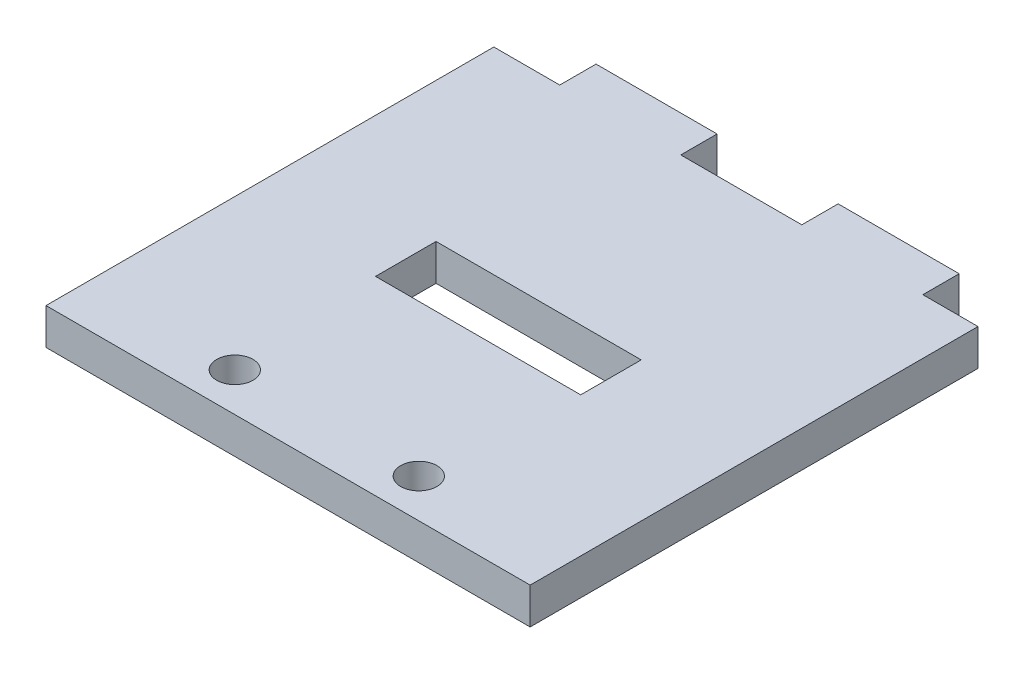
SolidWorks part; units mm, degrees
ref_plane "Front Plane" through (0, 0, 0) normal (0, 0, 1) x (1, 0, 0)
ref_plane "Top Plane" through (0, 0, 0) normal (0, 1, 0) x (1, 0, 0)
ref_plane "Right Plane" through (0, 0, 0) normal (1, 0, 0) x (0, 0, -1)
sketch "Sketch1" plane through (0, 0, 0) normal (0, 1, 0) x (1, 0, 0)
  line L1 (-20, 20) -> (20, 20)
  line L2 (-20, 20) -> (-20, -20)
  line L3 (-20, -20) -> (20, -20)
  line L4 (20, 20) -> (20, -20)
  line L5 (-20, 20) -> (20, -20) construction
  line L6 (-20, -20) -> (20, 20) construction
  point P0 (0, 0)
  dimension "D1" = 40
  dimension "D2" = 40
extrude "Boss-Extrude1" add sketch "Sketch1" along normal blind 3
sketch "Sketch2" plane through (0, 0, 0) normal (0, -1, 0) x (1, 0, 0)
  line L0 (-20, 16.8) -> (20, 16.8) construction
  line L1 (-20, -20) -> (-20, 20) construction
  line L2 (20, 20) -> (20, -20) construction
  line L3 (20, -20) -> (-20, -20) construction
  line L4 (0, 20) -> (0, -20) construction
  line L5 (-20, 20) -> (20, 20) construction
  line L7 (8.4755, -0.7) -> (-8.4755, -0.7)
  line L8 (8.4755, -0.7) -> (8.4755, 4.3)
  line L9 (8.4755, 4.3) -> (-8.4755, 4.3)
  line L10 (-8.4755, -0.7) -> (-8.4755, 4.3)
  line L11 (8.4755, -0.7) -> (-8.4755, 4.3) construction
  line L12 (8.4755, 4.3) -> (-8.4755, -0.7) construction
  circle A0 centre (7.6, 16.8) radius 1.5
  circle A1 centre (-7.6, 16.8) radius 1.5
  point P16 (0, 1.8)
  dimension "D6" = 3
  dimension "D7" = 3
  dimension "D1" = 21.8
  dimension "D2" = 7.6
  dimension "D3" = 7.6
  dimension "D4" = 17.5
  dimension "D5" = 5
extrude "Cut-Extrude2" cut sketch "Sketch2" against normal blind 10
sketch "Sketch5" plane through (0, 0, 0) normal (0, -1, 0) x (1, 0, 0)
  line L0 (20, -17) -> (15.4445, -17)
  line L1 (20, 20) -> (20, -20) construction
  line L2 (-20.6555, -17) -> (32.3445, -17) construction
  line L3 (15.4445, -17) -> (15.4445, -20)
  line L4 (20, -20) -> (-20, -20) construction
  line L5 (15.4445, -17) -> (15.4445, -20) construction
  line L6 (15.4445, -20) -> (5.4445, -20)
  line L7 (5.4445, -17) -> (5.4445, -20) construction
  line L8 (5.4445, -20) -> (5.4445, -17)
  line L9 (5.4445, -17) -> (-4.5555, -17)
  line L10 (-4.5555, -17) -> (-4.5555, -20)
  line L11 (-4.5555, -17) -> (-4.5555, -20) construction
  line L12 (-4.5555, -20) -> (-14.5555, -20)
  line L13 (-14.5555, -17) -> (-14.5555, -20) construction
  line L14 (-14.5555, -20) -> (-14.5555, -17)
  line L15 (-14.5555, -17) -> (-20, -17)
  line L16 (-20, -20) -> (-20, 20) construction
  line L17 (-20, -17) -> (-20, -21.558)
  line L18 (-20, -21.558) -> (20, -21.558)
  line L19 (20, -21.558) -> (20, -17)
extrude "Cut-Extrude3" cut sketch "Sketch5" against normal blind 10
